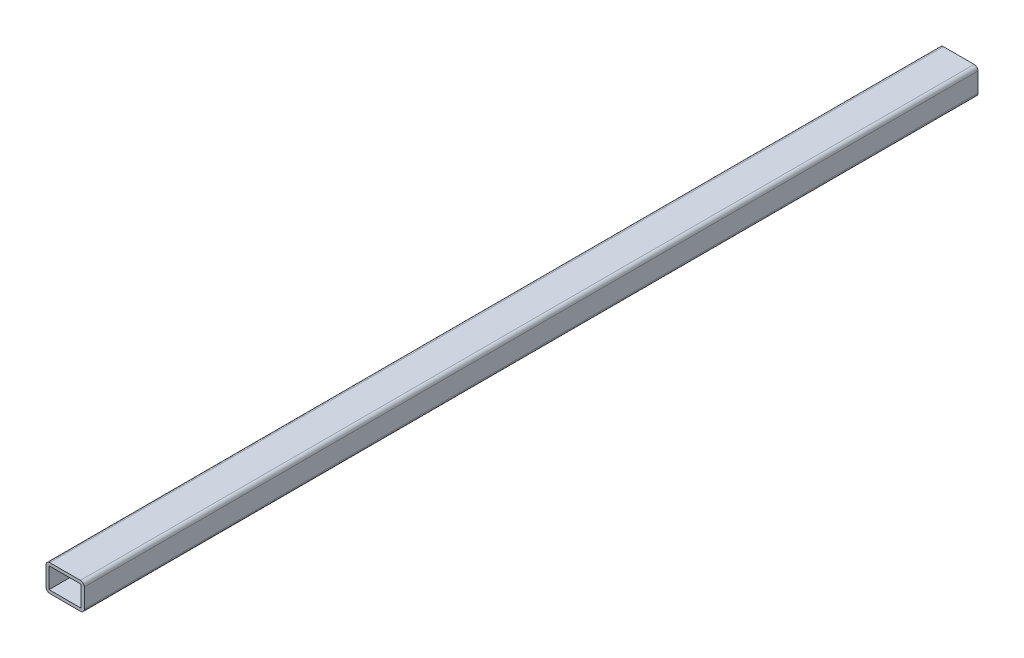
SolidWorks part; units mm, degrees
material "Gray Cast Iron"
ref_plane "Front Plane" through (0, 0, 0) normal (0, 0, 1) x (1, 0, 0)
ref_plane "Top Plane" through (0, 0, 0) normal (0, 1, 0) x (1, 0, 0)
ref_plane "Right Plane" through (0, 0, 0) normal (1, 0, 0) x (0, 0, -1)
sketch "Sketch1" plane through (0, 0, 0) normal (0, 0, 1) x (1, 0, 0)
  line L0 (3, 0) -> (27, 0)
  line L1 (30, 3) -> (30, 18)
  line L2 (27, 21) -> (3, 21)
  line L3 (0, 18) -> (0, 3)
  line L4 (2.4, 2.4) -> (27.6, 2.4)
  line L5 (27.6, 2.4) -> (27.6, 18.6)
  line L6 (27.6, 18.6) -> (2.4, 18.6)
  line L7 (2.4, 18.6) -> (2.4, 2.4)
  line L8 (0, 21) -> (0, 0) construction
  line L9 (30, 21) -> (0, 21) construction
  line L10 (0, 0) -> (30, 0) construction
  line L11 (30, 0) -> (30, 21) construction
  arc A0 (0, 18) -> (3, 21) centre (3, 18) cw
  arc A1 (3, 0) -> (0, 3) centre (3, 3) cw
  arc A2 (27, 0) -> (30, 3) centre (27, 3) ccw
  arc A3 (27, 21) -> (30, 18) centre (27, 18) cw
  point P12 (0, 21)
  dimension "D4" = 3
  dimension "D5" = 3
  dimension "D6" = 3
  dimension "D1" = 3
  dimension "D3" = 2.4
extrude "Boss-Extrude1" add sketch "Sketch1" along normal blind 700
